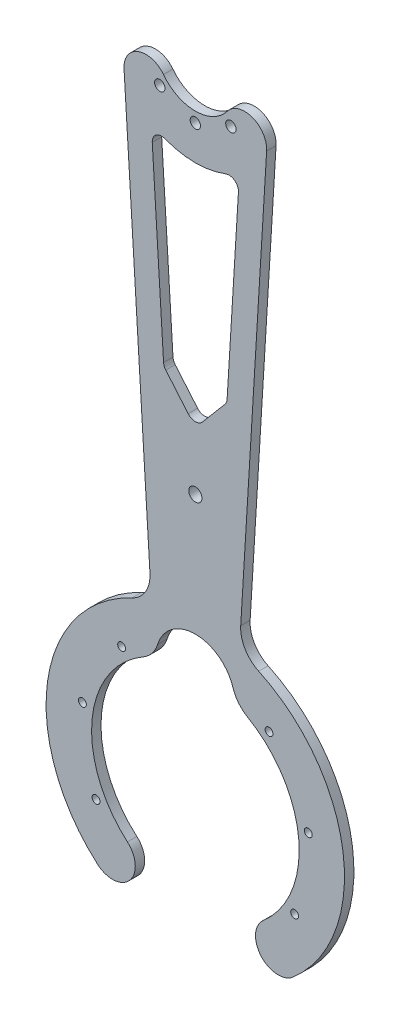
SolidWorks part; units mm, degrees
material "6061-O (SS)"
ref_plane "前视基准面" through (0, 0, 0) normal (0, 0, 1) x (1, 0, 0)
ref_plane "上视基准面" through (0, 0, 0) normal (0, 1, 0) x (1, 0, 0)
ref_plane "右视基准面" through (0, 0, 0) normal (1, 0, 0) x (0, 0, -1)
other "Configuration Table"
sketch "草图1" plane through (0, 0, 0) normal (0, 0, 1) x (1, 0, 0)
  line L0 (0, 0) -> (0, -21.9886) construction
  line L1 (0, 0) -> (-15.3152, -15.3152) construction
  line L2 (0, 0) -> (17.1443, -17.1443) construction
  line L3 (0, 50.5605) -> (0, -381.1612) construction
  line L4 (0, 0) -> (-15.4548, -4.1411) construction
  line L5 (-15.3152, -162.7971) -> (15.3152, -162.7971) construction
  line L6 (-14.4426, -147.3648) -> (-22.6976, -12.3955)
  line L7 (-13.5404, -162.1157) -> (0, -200.0384) construction
  line L8 (14.4404, -147.3996) -> (22.6976, -12.3955)
  line L9 (0, -200.0384) -> (13.5404, -162.1157) construction
  line L13 (26.3611, -230.4779) -> (-26.3611, -230.4779) construction
  circle A0 centre (0, 0) radius 16 construction
  circle A1 centre (0, 0) radius 12.75
  circle A2 centre (-11.3137, -11.3137) radius 1.65
  circle A3 centre (0, -16) radius 1.65
  circle A4 centre (11.3137, -11.3137) radius 1.65
  arc A6 (-10.1423, -7.7263) -> (-22.6976, -12.3955) centre (-15.7107, -11.9682) ccw
  arc A7 (10.1423, -7.7263) -> (22.6976, -12.3955) centre (15.7107, -11.9682) cw
  circle A8 centre (0, -200.0384) radius 33.0276 construction
  circle A10 centre (0, -200.0384) radius 40.2675 construction
  arc A11 (-15.3152, -162.7971) -> (-26.3611, -230.4779) centre (0, -200.0384) ccw construction
  arc A12 (-18.0688, -156.1013) -> (-31.1007, -235.9508) centre (0, -200.0384) ccw construction
  arc A13 (-12.5616, -169.4929) -> (-21.6215, -225.0051) centre (0, -200.0384) ccw construction
  arc A14 (-12.5616, -169.4929) -> (-18.0688, -156.1013) centre (-15.3152, -162.7971) ccw construction
  arc A15 (-31.1007, -235.9508) -> (-21.6215, -225.0051) centre (-26.3611, -230.4779) ccw construction
  arc A16 (15.3152, -162.7971) -> (26.3611, -230.4779) centre (0, -200.0384) cw construction
  arc A17 (31.0795, -235.9263) -> (18.0565, -156.1313) centre (0, -200.0384) ccw construction
  arc A18 (21.6427, -225.0296) -> (12.574, -169.4629) centre (0, -200.0384) ccw construction
  arc A19 (21.6427, -225.0296) -> (31.0795, -235.9263) centre (26.3611, -230.4779) ccw construction
  arc A20 (18.0565, -156.1313) -> (12.574, -169.4629) centre (15.3152, -162.7971) ccw construction
  arc A21 (-20.1768, -157.0286) -> (-31.1007, -235.9508) centre (0, -200.0384) ccw
  arc A22 (-21.6215, -225.0051) -> (-31.1007, -235.9508) centre (-26.3611, -230.4779) cw
  arc A23 (-21.6215, -225.0051) -> (-16.5415, -171.4516) centre (0, -200.0384) cw
  arc A24 (16.5459, -171.4167) -> (21.6427, -225.0296) centre (0, -200.0384) cw
  arc A25 (21.6427, -225.0296) -> (31.0795, -235.9263) centre (26.3611, -230.4779) ccw
  arc A26 (31.0795, -235.9263) -> (20.1727, -157.0624) centre (0, -200.0384) ccw
  arc A27 (-14.4426, -147.3648) -> (-20.1768, -157.0286) centre (-24.4239, -147.9753) cw
  arc A28 (14.4404, -147.3996) -> (20.1727, -157.0624) centre (24.4218, -148.01) ccw
  arc A29 (-11.9982, -165.7569) -> (12.0041, -165.7364) centre (0.0062, -169.4779) cw
  arc A30 (-16.5415, -171.4516) -> (-11.9982, -165.7569) centre (-21.5498, -162.7962) ccw
  arc A31 (12.0041, -165.7364) -> (16.5459, -171.4167) centre (21.5507, -162.7593) ccw
  point P15 (0, -220)
  point P22 (0, -220)
  point P30 (0, -165.3003)
  point P33 (0, -163.5756)
  point P35 (-39.7417, -193.5524)
  point P41 (39.7417, -193.5524)
  point P68 (-12.5616, -169.4929)
  point P71 (12.574, -169.4629)
  dimension "D1" = 32
  dimension "D2" = 25.5
  dimension "D5" = 3.3
  dimension "D6" = 3.3
  dimension "D7" = 3.3
  dimension "D12" = 14
  dimension "D8" = 10
  dimension "D10" = 10
  dimension "D11" = 10
  dimension "D13" = 10
  dimension "D3" = 45
  dimension "D4" = 45
  dimension "D9" = 75
extrude "凸台-拉伸1" add sketch "草图1" along normal blind 3
sketch "草图4" plane through (0, 0, 0) normal (0, 0, -1) x (-1, 0, 0)
  line L0 (-13.7159, -28.2019) -> (-10.1137, -87.0977)
  line L1 (-14.4404, -147.3996) -> (-22.6976, -12.3955) construction
  line L2 (0, 41.4898) -> (0, 27) construction
  line L3 (2.2925, -97.284) -> (9.4118, -88.8496)
  line L4 (0, -27) -> (0, -178.2536) construction
  line L5 (-2.2925, -97.284) -> (-9.4118, -88.8496)
  line L6 (13.7159, -28.2019) -> (10.1137, -87.0977)
  arc A0 (-9.6494, -25.2169) -> (9.6494, -25.2169) centre (0, 0) ccw
  arc A1 (13.7159, -28.2019) -> (9.6494, -25.2169) centre (10.7215, -28.0187) ccw
  arc A2 (-13.7159, -28.2019) -> (-9.6494, -25.2169) centre (-10.7215, -28.0187) cw
  arc A3 (9.4118, -88.8496) -> (10.1137, -87.0977) centre (7.1193, -86.9146) ccw
  arc A4 (2.2925, -97.284) -> (-2.2925, -97.284) centre (0, -95.349) cw
  arc A5 (-10.1137, -87.0977) -> (-9.4118, -88.8496) centre (-7.1193, -86.9146) ccw
  point P15 (14.0299, -23.0686)
  point P18 (-14.0299, -23.0686)
  point P22 (10.053, -88.09)
  point P25 (0, -100)
  point P28 (-10.053, -88.09)
  dimension "D2" = 54
  dimension "D3" = 3
  dimension "D6" = 3
  dimension "D1" = 8
  dimension "D4" = 100
  dimension "D5" = 60
extrude "切除-拉伸2" cut sketch "草图4" against normal blind 15
sketch "草图5" plane through (0, 0, 3) normal (0, 0, 1) x (1, 0, 0)
  line L0 (-12.2411, -94.7997) -> (-2.2925, -106.5861) construction
  line L1 (-9.4118, -88.8496) -> (-2.2925, -97.284) construction
  line L2 (-14.4426, -147.3648) -> (-22.6976, -12.3955) construction
  line L3 (-8.4988, -198.4027) -> (8.4988, -198.4027) construction
  line L4 (-17.528, -96.9179) -> (-11.4932, -195.5858) construction
  line L6 (17.528, -96.9179) -> (11.4932, -195.5858) construction
  line L7 (12.2411, -94.7997) -> (2.2925, -106.5861) construction
  line L8 (0, -107.651) -> (0, -201.1469) construction
  circle A0 centre (0, -188.4027) radius 2.1
  arc A1 (11.4932, -195.5858) -> (8.4988, -198.4027) centre (8.4988, -195.4027) cw construction
  arc A2 (-8.4988, -198.4027) -> (-11.4932, -195.5858) centre (-8.4988, -195.4027) cw construction
  arc A3 (2.2925, -106.5861) -> (-2.2925, -106.5861) centre (0, -104.651) cw construction
  arc A4 (17.528, -96.9179) -> (12.2411, -94.7997) centre (14.5336, -96.7348) ccw construction
  arc A5 (-12.2411, -94.7997) -> (-17.528, -96.9179) centre (-14.5336, -96.7348) ccw construction
  circle A6 centre (0, -118.4027) radius 2.1
  point P12 (-11.3209, -198.4027)
  point P23 (-18.0807, -87.8814)
  dimension "D2" = 3
  dimension "D3" = 4.2
  dimension "D4" = 4.2
  dimension "D5" = 10
  dimension "D6" = 70
  dimension "D1" = 6
extrude "切除-拉伸4" cut sketch "草图5" against normal blind 10
sketch "草图3" plane through (0, 0, 3) normal (0, 0, 1) x (1, 0, 0)
  line L0 (-10, -220) -> (-9.806, -223.1719)
  line L3 (0, -220) -> (0, -221.5633) construction
  line L5 (10, -220) -> (9.806, -223.1719)
  line L6 (-14.4426, -147.3648) -> (-22.6976, -12.3955) construction
  line L10 (-22.6976, -12.3955) -> (-14.4426, -147.3648)
  line L12 (14.4404, -147.3996) -> (22.6976, -12.3955)
  line L13 (-22.6976, -12.3955) -> (-14.4426, -147.3648)
  line L15 (14.4404, -147.3996) -> (22.6976, -12.3955)
  arc A0 (8.2741, -223.9564) -> (-8.2741, -223.9564) centre (0, -237.0633) ccw
  arc A1 (-9.806, -223.1719) -> (-8.2741, -223.9564) centre (-8.8079, -223.1108) ccw
  arc A2 (9.806, -223.1719) -> (8.2741, -223.9564) centre (8.8079, -223.1108) cw
  arc A6 (22.6976, -12.3955) -> (10.1423, -7.7263) centre (15.7107, -11.9682) ccw
  arc A7 (-10.1423, -7.7263) -> (10.1423, -7.7263) centre (0, 0) ccw
  arc A8 (-10.1423, -7.7263) -> (-22.6976, -12.3955) centre (-15.7107, -11.9682) ccw
  arc A9 (22.6976, -12.3955) -> (10.1423, -7.7263) centre (15.7107, -11.9682) ccw
  arc A10 (-10.1423, -7.7263) -> (10.1423, -7.7263) centre (0, 0) ccw
  arc A11 (-10.1423, -7.7263) -> (-22.6976, -12.3955) centre (-15.7107, -11.9682) ccw
  arc A23 (12.0041, -165.7364) -> (-11.9982, -165.7569) centre (0.0062, -169.4779) ccw
  arc A24 (12.0041, -165.7364) -> (-11.9982, -165.7569) centre (0.0062, -169.4779) ccw
  arc A25 (12.0041, -165.7364) -> (16.5459, -171.4167) centre (21.5507, -162.7593) ccw
  arc A26 (12.0041, -165.7364) -> (16.5459, -171.4167) centre (21.5507, -162.7593) ccw
  arc A27 (21.6427, -225.0296) -> (16.5459, -171.4167) centre (0, -200.0384) ccw
  arc A28 (21.6427, -225.0296) -> (16.5459, -171.4167) centre (0, -200.0384) ccw
  arc A29 (21.6427, -225.0296) -> (31.0795, -235.9263) centre (26.3611, -230.4779) ccw
  arc A30 (21.6427, -225.0296) -> (31.0795, -235.9263) centre (26.3611, -230.4779) ccw
  arc A31 (31.0795, -235.9263) -> (20.1727, -157.0624) centre (0, -200.0384) ccw
  arc A32 (31.0795, -235.9263) -> (20.1727, -157.0624) centre (0, -200.0384) ccw
  arc A33 (14.4404, -147.3996) -> (20.1727, -157.0624) centre (24.4218, -148.01) ccw
  arc A34 (14.4404, -147.3996) -> (20.1727, -157.0624) centre (24.4218, -148.01) ccw
  arc A35 (-20.1768, -157.0286) -> (-14.4426, -147.3648) centre (-24.4239, -147.9753) ccw
  arc A36 (-20.1768, -157.0286) -> (-14.4426, -147.3648) centre (-24.4239, -147.9753) ccw
  arc A37 (-20.1768, -157.0286) -> (-31.1007, -235.9508) centre (0, -200.0384) ccw
  arc A38 (-20.1768, -157.0286) -> (-31.1007, -235.9508) centre (0, -200.0384) ccw
  arc A39 (-31.1007, -235.9508) -> (-21.6215, -225.0051) centre (-26.3611, -230.4779) ccw
  arc A40 (-31.1007, -235.9508) -> (-21.6215, -225.0051) centre (-26.3611, -230.4779) ccw
  arc A41 (-16.5415, -171.4516) -> (-21.6215, -225.0051) centre (0, -200.0384) ccw
  arc A42 (-16.5415, -171.4516) -> (-21.6215, -225.0051) centre (0, -200.0384) ccw
  arc A43 (-16.5415, -171.4516) -> (-11.9982, -165.7569) centre (-21.5498, -162.7962) ccw
  arc A44 (-16.5415, -171.4516) -> (-11.9982, -165.7569) centre (-21.5498, -162.7962) ccw
  dimension "D1" = 31
  dimension "D2" = 2
  dimension "D3" = 3.1778
  dimension "D4" = 0
ref_plane "基准面1" through (0, 0, 3) normal (0, 0, 1) x (1, 0, 0)
sketch "草图7" plane through (0, 0, 3) normal (0, 0, 1) x (1, 0, 0)
  circle A0 centre (0, -200.0384) radius 36.5 construction
  circle A1 centre (0, -163.5384) radius 1.25
  circle A2 centre (23.4617, -172.0778) radius 1.25
  circle A3 centre (35.9455, -193.7003) radius 1.25
  circle A4 centre (31.6099, -218.2884) radius 1.25
  circle A5 centre (12.4837, -234.3372) radius 1.25
  circle A6 centre (-12.4837, -234.3372) radius 1.25
  circle A7 centre (-31.6099, -218.2884) radius 1.25
  circle A8 centre (-35.9455, -193.7003) radius 1.25
  circle A9 centre (-23.4617, -172.0778) radius 1.25
  dimension "D1" = 9
extrude "切除-拉伸5" cut sketch "草图7" against normal blind 10
